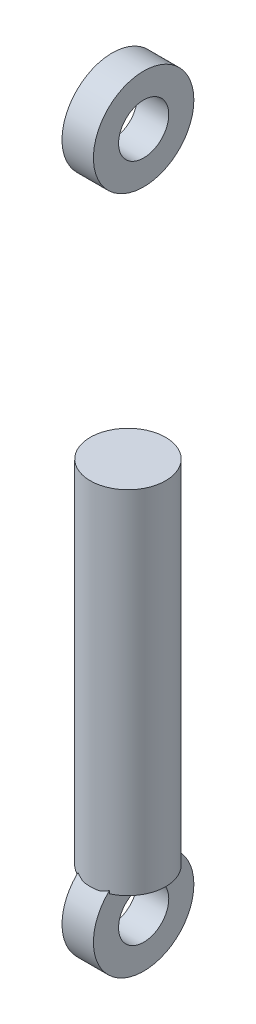
SolidWorks part; units mm, degrees
ref_plane "Front Plane" through (0, 0, 0) normal (0, 0, 1) x (1, 0, 0)
ref_plane "Top Plane" through (0, 0, 0) normal (0, 1, 0) x (1, 0, 0)
ref_plane "Right Plane" through (0, 0, 0) normal (1, 0, 0) x (0, 0, -1)
sketch "Sketch1" plane through (0, 0, 0) normal (0, 1, 0) x (1, 0, 0)
  circle A0 centre (0, 0) radius 3.81
  dimension "D1" = 7.62
extrude "Extrude1" add sketch "Sketch1" along normal blind 35.56
sketch "Sketch2" plane through (0, 35.56, 0) normal (0, 1, 0) x (1, 0, 0)
  circle A6 centre (0, 0) radius 10.16
  dimension "D1" = 20.32
sketch "Sketch4" plane through (0, 0, 0) normal (1, 0, 0) x (0, 0, -1)
  line L2 (0, -3.4405) -> (0, 65.2665) construction
  circle A0 centre (0, 65.2665) radius 2.54
  circle A1 centre (0, -3.4405) radius 2.54
  dimension "D3" = 5.08
  dimension "D4" = 68.707
extrude "Extrude-Thin1" add sketch "Sketch4" along normal mid plane 3.175 separate body thin
